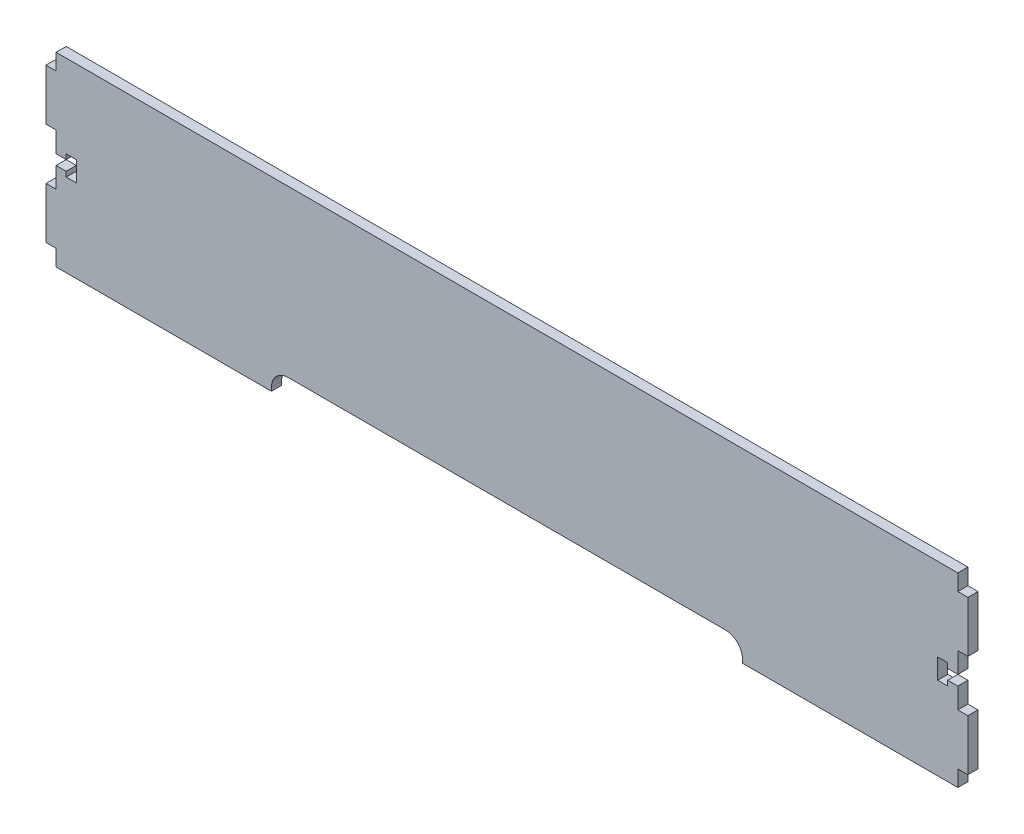
SolidWorks part; units mm, degrees
ref_plane "Alzado" through (0, 0, 0) normal (0, 0, 1) x (1, 0, 0)
ref_plane "Planta" through (0, 0, 0) normal (0, 1, 0) x (1, 0, 0)
ref_plane "Vista lateral" through (0, 0, 0) normal (1, 0, 0) x (0, 0, -1)
sketch "Croquis1" plane through (0, 0, 0) normal (0, 0, 1) x (1, 0, 0)
  line L0 (0, 27.625) -> (0, -21.595) construction
  line L1 (134, -27.625) -> (70, -27.625)
  line L2 (134, -27.625) -> (134, -1.5)
  line L3 (134, 27.625) -> (-134, 27.625)
  line L4 (-134, -27.625) -> (-134, -1.5)
  line L5 (134, -27.625) -> (-134, 27.625) construction
  line L6 (134, 27.625) -> (-134, -27.625) construction
  line L7 (65, -21.595) -> (-65, -21.595)
  line L8 (-70, -26.595) -> (-70, -27.625)
  line L9 (70, -26.595) -> (70, -27.625)
  line L10 (-70, -27.625) -> (-134, -27.625)
  line L11 (-134, 0) -> (-128, 0) construction
  line L12 (-128, -3) -> (-128, 3)
  line L13 (-128, 3) -> (-131, 3)
  line L14 (-131, 3) -> (-131, 1.5)
  line L15 (-131, 1.5) -> (-134, 1.5)
  line L16 (-131, -3) -> (-131, -1.5)
  line L17 (-128, -3) -> (-131, -3)
  line L18 (-131, -1.5) -> (-134, -1.5)
  line L19 (-134, 1.5) -> (-134, 27.625)
  line L20 (128, -3) -> (128, 3)
  line L21 (128, 3) -> (131, 3)
  line L22 (131, 3) -> (131, 1.5)
  line L23 (131, 1.5) -> (134, 1.5)
  line L24 (131, -3) -> (131, -1.5)
  line L25 (128, -3) -> (131, -3)
  line L26 (131, -1.5) -> (134, -1.5)
  line L27 (134, 1.5) -> (134, 27.625)
  arc A0 (65, -21.595) -> (70, -26.595) centre (65, -26.595) cw
  arc A1 (-65, -21.595) -> (-70, -26.595) centre (-65, -26.595) ccw
  point P0 (0, 0)
  point P11 (0, -21.595)
  point P15 (70, -21.595)
  point P18 (-70, -21.595)
  point P21 (-131, 0)
  dimension "D5" = 5
  dimension "D1" = 268
  dimension "D2" = 55.25
  dimension "D3" = 49.22
  dimension "D4" = 140
  dimension "D6" = 6
  dimension "D7" = 3
  dimension "D8" = 3
  dimension "D9" = 1.5
extrude "Saliente-Extruir1" add sketch "Croquis1" along normal blind 3
sketch "Croquis2" plane through (134, 0, 0) normal (1, 0, 0) x (0, 0, -1)
  line L0 (0, 1.5) -> (0, 27.625) construction
  line L1 (-3, 7.625) -> (0, 7.625)
  line L2 (-3, 7.625) -> (-3, 22.825)
  line L3 (-3, 22.825) -> (0, 22.825)
  line L4 (0, 7.625) -> (0, 22.825)
  line L5 (-3, 7.625) -> (0, 22.825) construction
  line L6 (-3, 22.825) -> (0, 7.625) construction
  line L7 (-3, 1.5) -> (-3, 27.625) construction
  line L11 (-3.25, 22.825) -> (-3.25, 7.625) construction
  line L12 (-3.25, 15.225) -> (0.25, 15.225) construction
  line L13 (0.25, 22.825) -> (0.25, 7.625) construction
  line L14 (0.25, 22.825) -> (-3.25, 22.825) construction
  line L15 (0, 0) -> (-5, 0) construction
  line L16 (-5, -27.625) -> (-5, 27.625) construction
  line L17 (0, -7.625) -> (0, -22.825)
  line L18 (-3, -22.825) -> (0, -22.825)
  line L19 (-3, -7.625) -> (-3, -22.825)
  line L20 (-3, -7.625) -> (0, -7.625)
  point P0 (-1.5, 15.225)
  point P19 (-1.5, 15.225)
extrude "Saliente-Extruir2" add sketch "Croquis2" along normal up to surface (3 mm away)
sketch "Croquis3" plane through (-134, 0, 0) normal (-1, 0, 0) x (0, 0, 1)
  line L0 (-0.25, 7.625) -> (-0.25, 22.825) construction
  line L1 (-0.25, 15.225) -> (3.25, 15.225) construction
  line L2 (3.25, 22.825) -> (3.25, 7.625) construction
  line L3 (0, 27.625) -> (0, 1.5) construction
  line L4 (3, 22.825) -> (0, 22.825)
  line L5 (3, 22.825) -> (3, 7.625)
  line L6 (3, 7.625) -> (0, 7.625)
  line L7 (0, 22.825) -> (0, 7.625)
  line L8 (3, 22.825) -> (0, 7.625) construction
  line L9 (3, 7.625) -> (0, 22.825) construction
  line L10 (-0.25, 7.625) -> (3.25, 7.625) construction
  line L11 (0, 0) -> (3, 0) construction
  line L12 (0, 3) -> (0, -3) construction
  line L13 (3, 3) -> (3, -3) construction
  line L14 (3, -7.625) -> (0, -7.625)
  line L15 (0, -22.825) -> (0, -7.625)
  line L16 (3, -22.825) -> (0, -22.825)
  line L17 (3, -22.825) -> (3, -7.625)
  point P8 (1.5, 15.225)
extrude "Saliente-Extruir3" add sketch "Croquis3" along normal up to surface (3 mm away)
